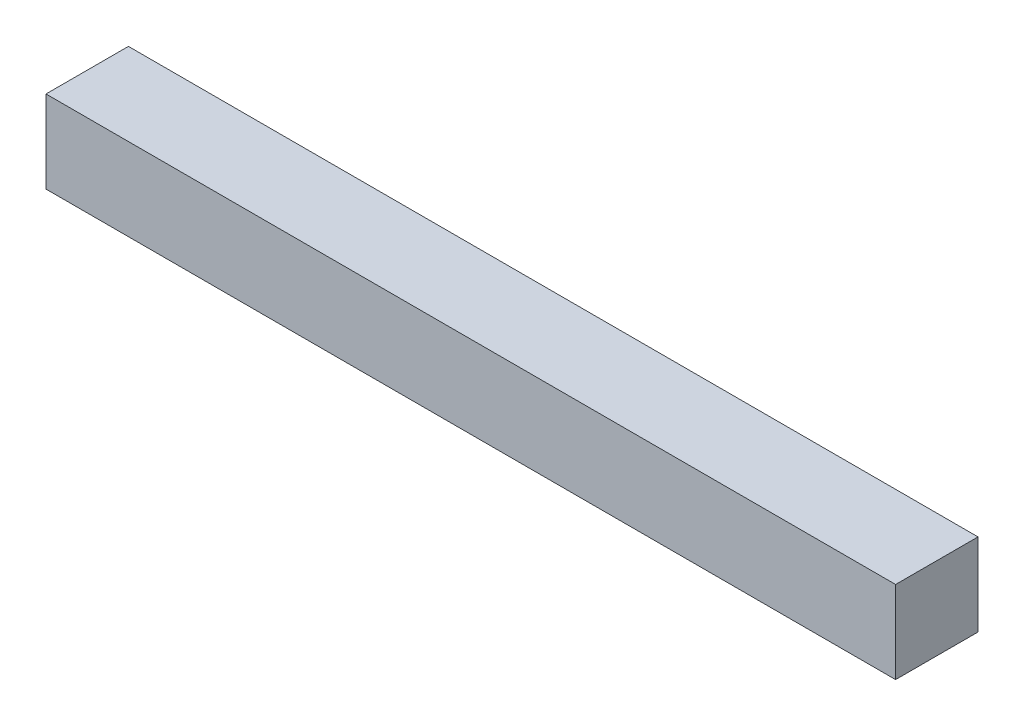
SolidWorks part; units mm, degrees
ref_plane "前视基准面" through (0, 0, 0) normal (0, 0, 1) x (1, 0, 0)
ref_plane "上视基准面" through (0, 0, 0) normal (0, 1, 0) x (1, 0, 0)
ref_plane "右视基准面" through (0, 0, 0) normal (1, 0, 0) x (0, 0, -1)
sketch "草图1" plane through (0, 0, 0) normal (0, 0, 1) x (1, 0, 0)
  line L1 (36.4593, 6.1281) -> (-13.5407, 6.1281)
  line L2 (36.4593, 6.1281) -> (36.4593, 1.2781)
  line L3 (36.4593, 1.2781) -> (-13.5407, 1.2781)
  line L4 (-13.5407, 6.1281) -> (-13.5407, 1.2781)
  line L5 (36.4593, 6.1281) -> (-13.5407, 1.2781) construction
  line L6 (36.4593, 1.2781) -> (-13.5407, 6.1281) construction
  point P0 (11.4593, 3.7031)
  dimension "D1" = 50
  dimension "D2" = 4.85
extrude "凸台-拉伸1" add sketch "草图1" along normal blind 4.85
